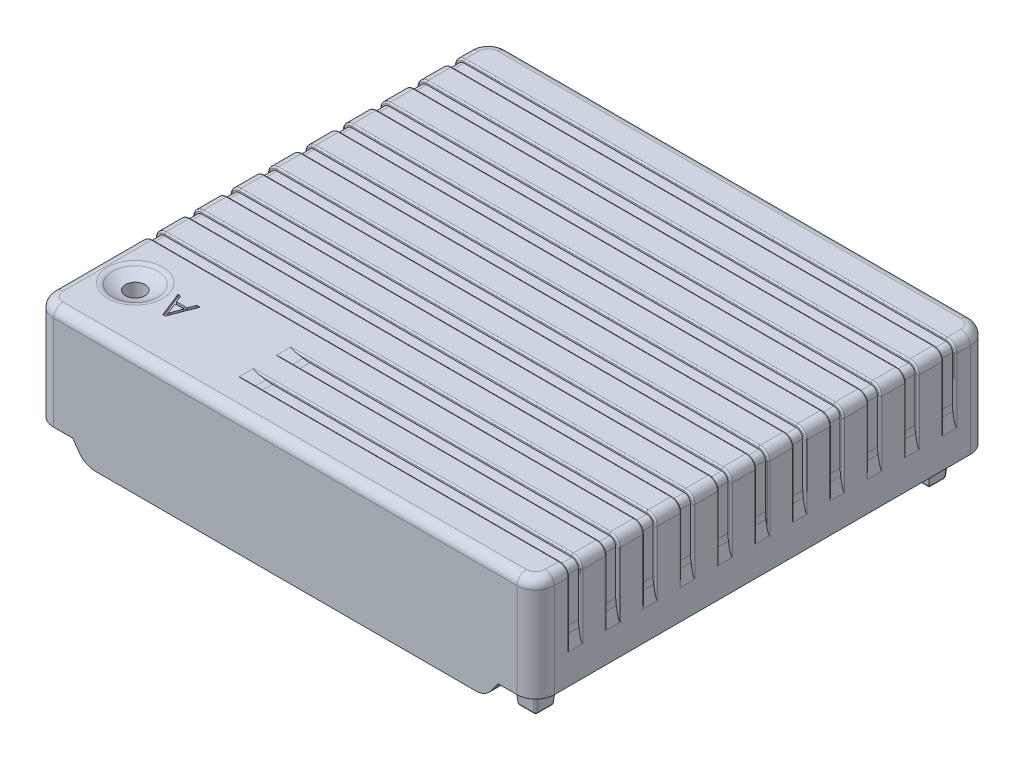
SolidWorks part; units mm, degrees
material "PPE"
ref_plane "Front Plane" through (0, 0, 0) normal (0, 0, 1) x (1, 0, 0)
ref_plane "Top Plane" through (0, 0, 0) normal (0, 1, 0) x (1, 0, 0)
ref_plane "Right Plane" through (0, 0, 0) normal (1, 0, 0) x (0, 0, -1)
sketch "Sketch1" plane through (0, 0, 0) normal (0, 1, 0) x (1, 0, 0)
  line L1 (39.325, -38.481) -> (-39.325, -38.481)
  line L2 (42.5, -35.306) -> (42.5, 35.306)
  line L3 (39.325, 38.481) -> (-39.325, 38.481)
  line L4 (-42.5, -35.306) -> (-42.5, 35.306)
  line L5 (42.5, -38.481) -> (-42.5, 38.481) construction
  line L6 (42.5, 38.481) -> (-42.5, -38.481) construction
  arc A0 (39.325, -38.481) -> (42.5, -35.306) centre (39.325, -35.306) ccw
  arc A1 (42.5, 35.306) -> (39.325, 38.481) centre (39.325, 35.306) ccw
  arc A2 (-39.325, 38.481) -> (-42.5, 35.306) centre (-39.325, 35.306) ccw
  arc A3 (-39.325, -38.481) -> (-42.5, -35.306) centre (-39.325, -35.306) cw
  point P0 (0, 0)
  dimension "D3" = 3.175
  dimension "D1" = 85
  dimension "D2" = 76.962
extrude "Boss-Extrude1" add sketch "Sketch1" along normal blind 10
sketch "Sketch2" plane through (0, 0, 0) normal (0, -1, 0) x (1, 0, 0)
  line L9 (39.325, 35.306) -> (-39.325, 35.306)
  line L10 (-39.325, 35.306) -> (-39.325, -35.306)
  line L11 (-39.325, -35.306) -> (39.325, -35.306)
  line L12 (39.325, -35.306) -> (39.325, 35.306)
  line L13 (39.325, 35.306) -> (-39.325, 35.306)
  line L14 (-39.325, 35.306) -> (-39.325, -35.306)
  line L15 (-39.325, -35.306) -> (39.325, -35.306)
  line L16 (39.325, -35.306) -> (39.325, 35.306)
  line L17 (39.325, 38.481) -> (-39.325, 38.481)
  line L18 (-42.5, 35.306) -> (-42.5, -35.306)
  line L19 (-39.325, -38.481) -> (39.325, -38.481)
  line L20 (42.5, -35.306) -> (42.5, 35.306)
  line L21 (39.325, 38.481) -> (-39.325, 38.481)
  line L22 (-42.5, 35.306) -> (-42.5, -35.306)
  line L23 (-39.325, -38.481) -> (39.325, -38.481)
  line L24 (42.5, -35.306) -> (42.5, 35.306)
  arc A8 (42.5, 35.306) -> (39.325, 38.481) centre (39.325, 35.306) ccw
  arc A9 (-39.325, 38.481) -> (-42.5, 35.306) centre (-39.325, 35.306) ccw
  arc A10 (-42.5, -35.306) -> (-39.325, -38.481) centre (-39.325, -35.306) ccw
  arc A11 (39.325, -38.481) -> (42.5, -35.306) centre (39.325, -35.306) ccw
  arc A12 (42.5, 35.306) -> (39.325, 38.481) centre (39.325, 35.306) ccw
  arc A13 (-39.325, 38.481) -> (-42.5, 35.306) centre (-39.325, 35.306) ccw
  arc A14 (-42.5, -35.306) -> (-39.325, -38.481) centre (-39.325, -35.306) ccw
  arc A15 (39.325, -38.481) -> (42.5, -35.306) centre (39.325, -35.306) ccw
  dimension "D1" = 3.175
  dimension "D2" = 0
extrude "Boss-Extrude2" add sketch "Sketch2" along normal blind 7.62
sketch "Sketch3" plane through (0, 0, 0) normal (0, -1, 0) x (1, 0, 0)
  line L0 (-39.325, 35.306) -> (-39.325, -35.306) construction
  line L1 (39.325, 35.306) -> (-39.325, 35.306) construction
  circle A0 centre (-36.023, 27.94) radius 1.651
  dimension "D1" = 3.302
  dimension "D2" = 3.302
  dimension "D3" = 7.366
extrude "Cut-Extrude1" cut sketch "Sketch3" against normal through all
sketch "Sketch4" plane through (0, 0, 0) normal (0, -1, 0) x (1, 0, 0)
  line L3 (-33.102, 30.3862) -> (-33.102, 25.4938)
  arc A3 (-33.102, 30.3862) -> (-33.102, 25.4938) centre (-36.023, 27.94) ccw
  circle A4 centre (-36.023, 27.94) radius 2.286
  dimension "D1" = 4.572
  dimension "D2" = 3.81
  dimension "D3" = 2.921
extrude "Boss-Extrude3" add sketch "Sketch4" along normal blind 10.16
fillet "Fillet1" radius 1.5875 8 edges at (-41.5701, 10, -37.5511) (0, 10, -38.481) (41.5701, 10, -37.5511) (42.5, 10, 0) (41.5701, 10, 37.5511) (0, 10, 38.481) (-41.5701, 10, 37.5511) (-42.5, 10, 0)
sketch "Sketch5" plane through (0, 0, 38.481) normal (0, 0, 1) x (1, 0, 0)
  line L0 (-35.896, -7.62) -> (-34.8876, -9.0601)
  line L1 (39.325, -7.62) -> (-39.325, -7.62) construction
  line L2 (-32.2868, -10.414) -> (32.2868, -10.414)
  line L3 (34.8876, -9.0601) -> (35.896, -7.62)
  line L4 (35.896, -7.62) -> (-35.896, -7.62)
  line L5 (0, 0) -> (0, -7.62) construction
  line L6 (0, -7.62) -> (0, -10.414) construction
  line L7 (-42.5, 8.4125) -> (-42.5, -7.62) construction
  arc A0 (32.2868, -10.414) -> (34.8876, -9.0601) centre (32.2868, -7.239) ccw
  arc A1 (-34.8876, -9.0601) -> (-32.2868, -10.414) centre (-32.2868, -7.239) ccw
  dimension "D4" = 3.175
  dimension "D1" = 6.604
  dimension "D2" = 35
  dimension "D3" = 2.794
extrude "Boss-Extrude4" add sketch "Sketch5" against normal up to surface (3.175 mm away) up to face at (0, -3.81, 35.306)
sketch "Sketch9" plane through (0, 0, -38.481) normal (0, 0, -1) x (-1, 0, 0)
  line L0 (39.325, -7.62) -> (-39.325, -7.62) construction
  line L1 (-23.45, -7.62) -> (23.45, -7.62)
  line L2 (-23.45, -7.62) -> (-23.45, -6.0325)
  line L3 (-21.8625, -4.445) -> (21.8625, -4.445)
  line L4 (23.45, -7.62) -> (23.45, -6.0325)
  line L5 (-42.5, 8.4125) -> (-42.5, -7.62) construction
  line L7 (42.5, 8.4125) -> (42.5, -7.62) construction
  arc A0 (21.8625, -4.445) -> (23.45, -6.0325) centre (21.8625, -6.0325) cw
  arc A1 (-23.45, -6.0325) -> (-21.8625, -4.445) centre (-21.8625, -6.0325) cw
  point P8 (-42.5, 0.3963)
  point P9 (0, -7.62)
  dimension "D3" = 1.5875
  dimension "D1" = 19.05
  dimension "D2" = 19.05
  dimension "D4" = 3.175
extrude "Cut-Extrude5" [suppressed] cut sketch "Sketch9" against normal up to next
ref_plane "Plane1" through (0, 0, 27.94) normal (0, 0, 1) x (1, 0, 0)
sketch "Sketch11" plane through (0, 0, 27.94) normal (0, 0, 1) x (1, 0, 0)
  line L0 (-36.023, 8.2345) -> (-36.023, -4.4948) construction
  line L1 (-36.023, -10.16) -> (-36.023, 0) construction
  line L2 (-39.325, 10) -> (-40.9125, 10) construction
  line L3 (-36.023, 8.73) -> (-27.2849, 8.73) construction
  line L4 (-39.325, 10) -> (39.325, 10) construction
  line L5 (-40.214, 10) -> (-36.023, 10)
  line L6 (-36.023, 10) -> (-36.023, 8.73)
  arc A0 (-36.023, 8.73) -> (-40.214, 10) centre (-36.023, 16.2801) cw
  dimension "D2" = 4.191
  dimension "D1" = 1.27
revolve "Cut-Revolve1" cut sketch "Sketch11" angle 360 about L0
fillet "Fillet2" radius 1.5875 1 edges at (-36.023, 10, 32.131)
sketch "Sketch13" plane through (0, 0, 0) normal (0, -1, 0) x (1, 0, 0)
  line L0 (-39.325, 35.306) -> (-39.325, 29.8408)
  line L1 (39.325, 35.306) -> (35.515, 35.306)
  line L2 (39.325, 35.306) -> (39.325, 31.496)
  line L3 (39.325, 31.496) -> (35.515, 31.496)
  line L4 (35.515, 35.306) -> (35.515, 31.496)
  line L5 (39.325, -35.306) -> (35.515, -35.306)
  line L6 (39.325, -35.306) -> (39.325, -31.496)
  line L7 (39.325, -31.496) -> (35.515, -31.496)
  line L8 (35.515, -35.306) -> (35.515, -31.496)
  line L9 (-39.325, -35.306) -> (-35.515, -35.306)
  line L10 (-39.325, -35.306) -> (-39.325, -31.496)
  line L11 (-39.325, -31.496) -> (-35.515, -31.496)
  line L12 (-35.515, -35.306) -> (-35.515, -31.496)
  line L13 (-39.325, 35.306) -> (-35.7599, 35.306)
  line L14 (-39.325, 35.306) -> (-39.325, 29.8408) construction
  line L16 (-35.7599, 35.306) -> (-35.7599, 31.7409)
  arc A0 (-33.102, 30.3862) -> (-33.102, 25.4938) centre (-36.023, 27.94) ccw construction
  arc A1 (-35.7599, 31.7409) -> (-39.325, 29.8408) centre (-36.023, 27.94) ccw
  dimension "D1" = 3.81
extrude "Boss-Extrude5" add sketch "Sketch13" along normal up to surface (7.62 mm away) up to face at (-4.3977, -7.62, 11.303)
sketch "Sketch14" plane through (0, -7.62, 0) normal (0, -1, 0) x (1, 0, 0)
  line L0 (-35.515, -35.306) -> (35.515, -35.306) construction
  line L1 (-39.325, -31.496) -> (-35.515, -31.496)
  line L2 (-39.325, -31.496) -> (-39.325, -35.306)
  line L3 (-39.325, -35.306) -> (-35.515, -35.306)
  line L4 (-35.515, -31.496) -> (-35.515, -35.306)
  line L5 (-39.325, 26.0392) -> (-39.325, -31.496) construction
  line L6 (39.325, -31.496) -> (35.515, -31.496)
  line L7 (39.325, -31.496) -> (39.325, -35.306)
  line L8 (39.325, -35.306) -> (35.515, -35.306)
  line L9 (35.515, -31.496) -> (35.515, -35.306)
  line L10 (35.515, 35.306) -> (39.325, 35.306)
  line L11 (35.515, 35.306) -> (35.515, 31.496)
  line L12 (35.515, 31.496) -> (39.325, 31.496)
  line L13 (39.325, 35.306) -> (39.325, 31.496)
  line L14 (-35.7599, 35.306) -> (-39.325, 35.306)
  line L15 (-35.7599, 35.306) -> (-35.7599, 31.496)
  line L16 (-35.7599, 31.496) -> (-39.325, 31.496)
  line L17 (-39.325, 35.306) -> (-39.325, 31.496)
extrude "Boss-Extrude6" add sketch "Sketch14" along normal blind 5.08 draft 5
fillet "Fillet3" radius 0.381 20 edges at (-37.5425, -12.7, 31.9404) (-38.8806, -12.7, 33.401) (-37.5425, -12.7, 34.8616) (-36.2043, -12.7, 33.401) (37.42, -12.7, 34.8616) (38.8806, -12.7, 33.401) (37.42, -12.7, 31.9404) (35.9594, -12.7, 33.401) (37.42, -12.7, -34.8616) (35.9594, -12.7, -33.401) (37.42, -12.7, -31.9404) (38.8806, -12.7, -33.401) (-37.42, -12.7, -31.9404) (-35.9594, -12.7, -33.401) (-37.42, -12.7, -34.8616) (-38.8806, -12.7, -33.401) (-39.1028, -10.16, 35.0838) (39.1028, -10.16, 35.0838) (39.1028, -10.16, -35.0838) (-39.1028, -10.16, -35.0838)
sketch "Sketch15" plane through (0, 0, 0) normal (0, 0, 1) x (1, 0, 0)
  line L0 (39.325, -0.2124) -> (40.468, -3.3528)
  line L1 (39.325, 8.4125) -> (39.325, -7.62) construction
  line L2 (40.468, -3.3528) -> (40.468, -4.1148)
  line L3 (40.468, -4.1148) -> (39.325, -5.2578)
  line L4 (39.325, -5.2578) -> (39.325, -0.2124)
  line L6 (39.325, -7.62) -> (42.5, -7.62) construction
  dimension "D1" = 2.3622
  dimension "D2" = 45
  dimension "D3" = 20
  dimension "D4" = 0.762
  dimension "D5" = 1.143
extrude "Cut-Extrude7" cut sketch "Sketch15" against normal blind 11.049 from offset 18.288 offset against normal yes
mirror "Mirror1" about plane through (0, 0, 0) normal (1, 0, 0) of "Cut-Extrude7"
pattern_linear "LPattern1" count 2 spacing 47.625 along (0, 0, 1) of "Cut-Extrude7"
ref_plane "Plane2" through (0, 0, 5.588) normal (0, 0, 1) x (1, 0, 0)
sketch "Sketch16" plane through (0, 0, 5.588) normal (0, 0, 1) x (1, 0, 0)
  line L5 (-39.325, -5.2578) -> (-39.325, -0.2124)
  line L6 (-39.325, -0.2124) -> (-40.468, -3.3528)
  line L7 (-40.468, -3.3528) -> (-40.468, -4.1148)
  line L8 (-40.468, -4.1148) -> (-39.325, -5.2578)
  line L9 (-39.325, -5.2578) -> (-39.325, -0.2124)
  line L10 (-39.325, -0.2124) -> (-40.468, -3.3528)
  line L11 (-40.468, -3.3528) -> (-40.468, -4.1148)
  line L12 (-40.468, -4.1148) -> (-39.325, -5.2578)
  dimension "D1" = 0
extrude "Cut-Extrude8" cut sketch "Sketch16" along normal blind 11.049
sketch "Sketch17" plane through (0, 10, 0) normal (0, 1, 0) x (1, 0, 0)
  line L1 (-26.879, -26.035) -> (-33.645, -26.035) construction
  circle A4 centre (-36.023, -27.94) radius 1.651 construction
  text T1 "A" font "@Adobe Fan Heiti Std B" height in points 14
  dimension "D3" = 9.144
extrude "Cut-Extrude9" cut sketch "Sketch17" against normal blind 0.381
sketch "Sketch18" plane through (0, 0, 0) normal (0, 0, 1) x (1, 0, 0)
  line L0 (-42.5, -2.54) -> (-42.0885, -0.2061)
  line L1 (-42.5, 8.4125) -> (-42.5, -7.62) construction
  line L10 (-42.5, 8.4125) -> (-42.5, -7.62) construction
  line L11 (-39.325, 10) -> (-40.9125, 10) construction
  line L12 (39.325, 10) -> (-39.325, 10) construction
  line L13 (40.9125, 10) -> (39.325, 10) construction
  line L14 (42.5, 8.4125) -> (42.5, -7.62) construction
  line L15 (-41.992, -7.62) -> (-41.992, 8.4125)
  line L16 (-40.9125, 9.492) -> (-39.325, 9.492)
  line L17 (-39.325, 9.492) -> (39.325, 9.492)
  line L18 (39.325, 9.492) -> (40.9125, 9.492)
  line L19 (41.992, 8.4125) -> (41.992, -7.62)
  line L20 (-41.992, 0.8966) -> (-41.992, 8.4125)
  line L21 (-40.9125, 9.492) -> (-39.325, 9.492)
  line L22 (-39.325, 9.492) -> (39.325, 9.492)
  line L23 (39.325, 9.492) -> (40.9125, 9.492)
  line L24 (41.992, 8.4125) -> (41.992, 0.8966)
  line L25 (-42.5, 8.4125) -> (-42.5, -2.54)
  line L26 (-39.325, 10) -> (-40.9125, 10)
  line L27 (39.325, 10) -> (-39.325, 10)
  line L28 (40.9125, 10) -> (39.325, 10)
  line L29 (42.5, 8.4125) -> (42.5, -2.54)
  line L30 (42.5, -2.54) -> (42.0885, -0.2061)
  line L31 (39.325, -7.62) -> (42.5, -7.62) construction
  arc A5 (-40.9125, 10) -> (-42.5, 8.4125) centre (-40.9125, 8.4125) ccw construction
  arc A6 (42.5, 8.4125) -> (40.9125, 10) centre (40.9125, 8.4125) ccw construction
  arc A7 (-40.9125, 9.492) -> (-41.992, 8.4125) centre (-40.9125, 8.4125) ccw
  arc A8 (41.992, 8.4125) -> (40.9125, 9.492) centre (40.9125, 8.4125) ccw
  arc A9 (-40.9125, 9.492) -> (-41.992, 8.4125) centre (-40.9125, 8.4125) ccw
  arc A10 (41.992, 8.4125) -> (40.9125, 9.492) centre (40.9125, 8.4125) ccw
  arc A11 (-40.9125, 10) -> (-42.5, 8.4125) centre (-40.9125, 8.4125) ccw
  arc A12 (42.5, 8.4125) -> (40.9125, 10) centre (40.9125, 8.4125) ccw
  arc A13 (42.0885, -0.2061) -> (41.992, 0.8966) centre (48.342, 0.8966) cw
  arc A14 (-42.0885, -0.2061) -> (-41.992, 0.8966) centre (-48.342, 0.8966) ccw
  point P20 (41.992, 0.341)
  point P23 (-41.992, 0.341)
  dimension "D4" = 6.35
  dimension "D2" = 5.08
  dimension "D3" = 10
  dimension "D1" = 0.508
extrude "Cut-Extrude10" cut sketch "Sketch18" against normal mid plane 2.032
fillet "Fillet4" radius 0.254 10 edges at (42.5, 2.9363, 1.016) (-42.5, 2.9363, 1.016) (-42.035, 9.535, 1.016) (0, 10, 1.016) (-42.5, 2.9363, -1.016) (-42.035, 9.535, -1.016) (0, 10, -1.016) (42.035, 9.535, -1.016) (42.035, 9.535, 1.016) (42.5, 2.9363, -1.016)
pattern_linear "LPattern2" count 6 spacing 6.35 along (0, 0, -1) of "Cut-Extrude10", "Fillet4"
pattern_linear "LPattern3" count 4 spacing 6.35 along (0, 0, 1) of "Cut-Extrude10", "Fillet4"
ref_plane "Plane3" through (0, 0, 24.384) normal (0, 0, 1) x (1, 0, 0)
sketch "Sketch19" plane through (0, 0, 24.384) normal (0, 0, 1) x (1, 0, 0)
  line L0 (-11.0461, 9.5885) -> (-13.38, 10)
  line L1 (42.5, -2.54) -> (42.246, -1.0995) construction
  line L2 (42.0885, -0.2061) -> (42.246, -1.0995) construction
  line L3 (41.992, 8.4125) -> (41.992, 0.8966) construction
  line L4 (-40.9125, 9.492) -> (40.9125, 9.492) construction
  line L5 (42.5, -2.54) -> (42.246, -1.0995)
  line L6 (42.0885, -0.2061) -> (42.246, -1.0995)
  line L7 (41.992, 8.4125) -> (41.992, 0.8966)
  line L8 (-9.9434, 9.492) -> (40.9125, 9.492)
  line L9 (-39.325, 10) -> (39.325, 10) construction
  line L10 (40.9125, 10) -> (39.325, 10) construction
  line L11 (42.5, 8.4125) -> (42.5, -7.62) construction
  line L12 (-13.38, 10) -> (39.325, 10)
  line L13 (40.9125, 10) -> (39.325, 10)
  line L14 (42.5, 8.4125) -> (42.5, -2.54)
  arc A0 (41.992, 0.8966) -> (42.0885, -0.2061) centre (48.342, 0.8966) ccw construction
  arc A1 (41.992, 8.4125) -> (40.9125, 9.492) centre (40.9125, 8.4125) ccw construction
  arc A2 (41.992, 0.8966) -> (42.0885, -0.2061) centre (48.342, 0.8966) ccw
  arc A3 (41.992, 8.4125) -> (40.9125, 9.492) centre (40.9125, 8.4125) ccw
  arc A4 (42.5, 8.4125) -> (40.9125, 10) centre (40.9125, 8.4125) ccw construction
  arc A5 (42.5, 8.4125) -> (40.9125, 10) centre (40.9125, 8.4125) ccw
  arc A6 (-11.0461, 9.5885) -> (-9.9434, 9.492) centre (-9.9434, 15.842) ccw
  dimension "D3" = 6.35
  dimension "D1" = 10
  dimension "D2" = 55.88
extrude "Cut-Extrude11" cut sketch "Sketch19" along normal blind 2.032
fillet "Fillet5" radius 0.254 6 edges at (13.7662, 10, 26.416) (42.035, 9.535, 26.416) (13.7662, 10, 24.384) (42.035, 9.535, 24.384) (42.5, 2.9363, 26.416) (42.5, 2.9363, 24.384)
pattern_linear "LPattern4" count 2 spacing 6.35 along (0, 0, 1) of "Cut-Extrude11", "Fillet5"
sketch "Sketch20" plane through (0, 0, 0) normal (0, -1, 0) x (1, 0, 0)
  line L12 (-35.7599, 35.306) -> (-35.7599, 31.7409)
  line L13 (-35.7599, 35.306) -> (-35.7599, 31.7409)
  line L14 (-33.102, 30.3862) -> (-33.102, 25.4938)
  line L15 (-33.102, 30.3862) -> (-33.102, 25.4938)
  line L16 (-39.325, 26.0392) -> (-39.325, -31.496)
  line L17 (-39.325, 26.0392) -> (-39.325, -31.496)
  line L18 (-39.325, -31.496) -> (-35.515, -31.496)
  line L19 (-39.325, -31.496) -> (-35.515, -31.496)
  line L20 (-35.515, -31.496) -> (-35.515, -35.306)
  line L21 (-35.515, -31.496) -> (-35.515, -35.306)
  line L22 (-35.515, -35.306) -> (35.515, -35.306)
  line L23 (-35.515, -35.306) -> (35.515, -35.306)
  line L36 (35.515, -35.306) -> (35.515, -31.496)
  line L37 (35.515, -35.306) -> (35.515, -31.496)
  line L38 (35.515, -31.496) -> (39.325, -31.496)
  line L39 (35.515, -31.496) -> (39.325, -31.496)
  line L40 (39.325, -31.496) -> (39.325, 31.496)
  line L41 (39.325, -31.496) -> (39.325, 31.496)
  line L42 (39.325, 31.496) -> (35.515, 31.496)
  line L43 (39.325, 31.496) -> (35.515, 31.496)
  line L44 (35.515, 31.496) -> (35.515, 35.306)
  line L45 (35.515, 31.496) -> (35.515, 35.306)
  line L46 (35.515, 35.306) -> (-35.7599, 35.306)
  line L47 (35.515, 35.306) -> (-35.7599, 35.306)
  arc A1 (-33.102, 30.3862) -> (-35.7599, 31.7409) centre (-36.023, 27.94) ccw
  arc A6 (-33.102, 30.3862) -> (-35.7599, 31.7409) centre (-36.023, 27.94) ccw
  arc A7 (-39.325, 26.0392) -> (-33.102, 25.4938) centre (-36.023, 27.94) ccw
  arc A8 (-39.325, 26.0392) -> (-33.102, 25.4938) centre (-36.023, 27.94) ccw
  dimension "D1" = 0
extrude "Cut-Extrude12" cut sketch "Sketch20" against normal blind 8.49
sketch "Sketch21" plane through (0, -10.16, 0) normal (0, -1, 0) x (1, 0, 0)
  line L6 (-35.9821, 31.7498) -> (-35.9821, 31.7182)
  line L7 (-35.9821, 31.7182) -> (-36.5141, 31.7182)
  line L8 (-33.102, 25.4938) -> (-33.102, 30.3862)
  line L9 (-35.9821, 31.7498) -> (-35.9821, 31.7182)
  line L10 (-35.9821, 31.7182) -> (-36.5141, 31.7182)
  line L11 (-33.102, 25.4938) -> (-33.102, 30.3862)
  arc A4 (-33.102, 30.3862) -> (-35.9821, 31.7498) centre (-36.023, 27.94) ccw
  arc A5 (-36.5141, 31.7182) -> (-33.102, 25.4938) centre (-36.023, 27.94) ccw
  arc A6 (-33.102, 30.3862) -> (-35.9821, 31.7498) centre (-36.023, 27.94) ccw
  arc A7 (-36.5141, 31.7182) -> (-33.102, 25.4938) centre (-36.023, 27.94) ccw
  dimension "D1" = 0
extrude "Cut-Extrude13" cut sketch "Sketch21" against normal blind 3
sketch "Sketch22" plane through (0, 0, 38.481) normal (0, 0, 1) x (1, 0, 0)
  line L3 (-36.0189, -7.706) -> (-36.0791, -7.62)
  line L4 (-35.896, -7.62) -> (-39.325, -7.62) construction
  line L5 (36.0189, -7.706) -> (36.0791, -7.62)
  line L6 (-36.0189, -7.706) -> (-35.0105, -9.1461)
  line L7 (-32.2868, -10.564) -> (32.2868, -10.564)
  line L8 (35.0105, -9.1461) -> (36.0189, -7.706)
  line L9 (-36.0189, -7.706) -> (-35.0105, -9.1461)
  line L10 (-32.2868, -10.564) -> (32.2868, -10.564)
  line L11 (35.0105, -9.1461) -> (36.0189, -7.706)
  line L12 (39.325, -7.62) -> (35.896, -7.62) construction
  line L13 (36.0791, -7.62) -> (-36.0791, -7.62)
  arc A4 (-35.0105, -9.1461) -> (-32.2868, -10.564) centre (-32.2868, -7.239) ccw
  arc A5 (32.2868, -10.564) -> (35.0105, -9.1461) centre (32.2868, -7.239) ccw
  arc A6 (-35.0105, -9.1461) -> (-32.2868, -10.564) centre (-32.2868, -7.239) ccw
  arc A7 (32.2868, -10.564) -> (35.0105, -9.1461) centre (32.2868, -7.239) ccw
  dimension "D1" = 0.15
extrude "Boss-Extrude7" add sketch "Sketch22" against normal up to surface (3.175 mm away)
